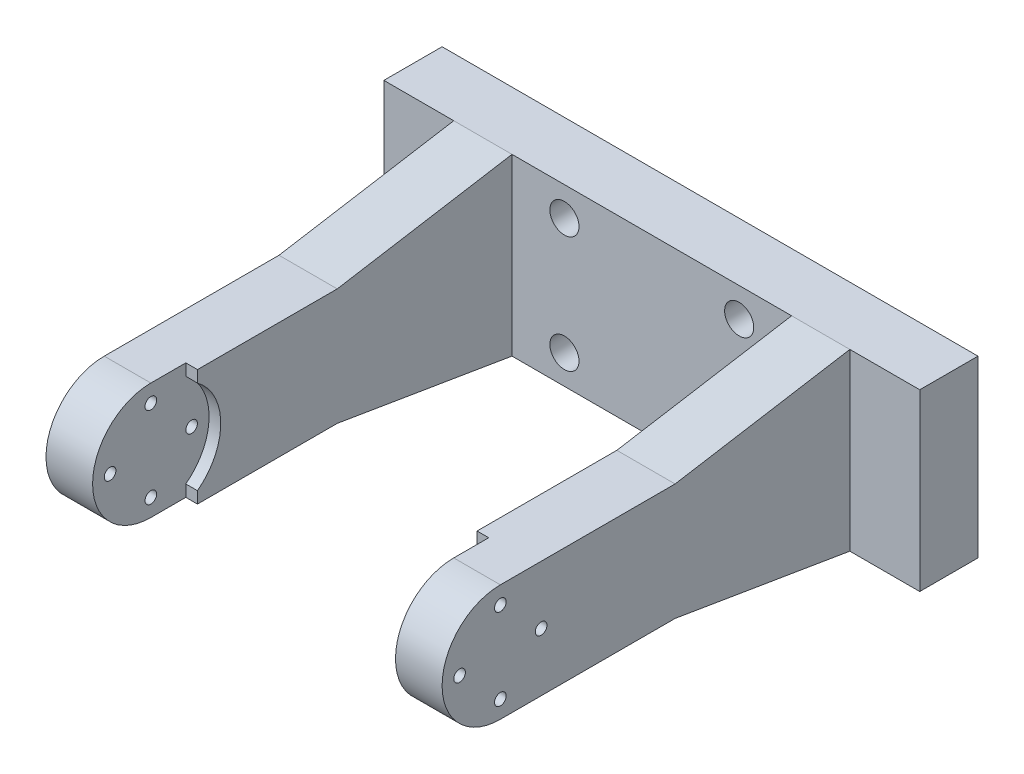
SolidWorks part; units mm, degrees
ref_plane "Front Plane" through (0, 0, 0) normal (0, 0, 1) x (1, 0, 0)
ref_plane "Top Plane" through (0, 0, 0) normal (0, 1, 0) x (1, 0, 0)
ref_plane "Right Plane" through (0, 0, 0) normal (1, 0, 0) x (0, 0, -1)
sketch "Sketch1" plane through (0, 0, 0) normal (0, 0, 1) x (1, 0, 0)
  line L1 (-46, -15) -> (46, -15)
  line L2 (-46, -15) -> (-46, 15)
  line L3 (-46, 15) -> (46, 15)
  line L4 (46, -15) -> (46, 15)
  line L5 (-46, -15) -> (46, 15) construction
  line L6 (-46, 15) -> (46, -15) construction
  point P0 (0, 0)
  dimension "D1" = 92
  dimension "D2" = 30
extrude "Boss-Extrude1" add sketch "Sketch1" along normal blind 10
sketch "Sketch2" plane through (46, 0, 0) normal (1, 0, 0) x (0, 0, -1)
  line L0 (-10, 15) -> (-40, 10)
  line L1 (-40, 10) -> (-70, 10)
  line L2 (-70, 10) -> (-70, -10) construction
  line L3 (-70, -10) -> (-40, -10)
  line L4 (-40, -10) -> (-10, -15)
  line L5 (0, -15) -> (0, 15) construction
  circle A0 centre (-70, 0) radius 10
  line M7 (-10, 15) -> (-10, -15)
  dimension "D1" = 20
  dimension "D2" = 70
  dimension "D3" = 30
extrude "Boss-Extrude2" add sketch "Sketch2" against normal blind 10 from offset 12 contours A0 L3 L4 L0 L1 M7 | A0 L2 | L2 A0 offset against normal yes
sketch "Sketch3" plane through (34, 0, 0) normal (1, 0, 0) x (0, 0, -1)
  circle A0 centre (-70, 0) radius 10 construction
  circle A1 centre (-70, 0) radius 7 construction
  circle A2 centre (-70, 7) radius 1
  circle A3 centre (-63, 0) radius 1
  circle A4 centre (-70, -7) radius 1
  circle A5 centre (-77, 0) radius 1
  dimension "D1" = 14
  dimension "D2" = 2
  dimension "D3" = 4
extrude "Cut-Extrude1" cut sketch "Sketch3" against normal blind 10
mirror "Mirror1" about plane through (0, 0, 0) normal (1, 0, 0) of "Boss-Extrude2", "Cut-Extrude1"
sketch "Sketch6" plane through (24, 0, 0) normal (-1, 0, 0) x (0, 0, 1)
  line L0 (70, 10) -> (64, 10)
  line L1 (40, 10) -> (70, 10) construction
  line L2 (64, 10) -> (64, 8)
  line L4 (64, -8) -> (64, -10)
  line L5 (70, -10) -> (40, -10) construction
  line L6 (64, -10) -> (70, -10)
  arc A0 (64, 8) -> (64, -8) centre (70, 0) ccw
  arc A1 (70, -10) -> (70, 10) centre (70, 0) ccw
  dimension "D1" = 2
extrude "Cut-Extrude2" cut sketch "Sketch6" against normal blind 2
mirror "Mirror2" about plane through (0, 0, 0) normal (1, 0, 0) of "Cut-Extrude2"
sketch "Sketch7" plane through (0, 0, 10) normal (0, 0, 1) x (1, 0, 0)
  line L0 (15, 10) -> (-15, 10) construction
  line L4 (-15, -10) -> (15, -10) construction
  circle A1 centre (-15, 10) radius 2.5
  circle A2 centre (15, 10) radius 2.5
  circle A4 centre (-15, -10) radius 2.5
  circle A5 centre (15, -10) radius 2.5
  point P11 (0, 10)
  dimension "D1" = 5
  dimension "D2" = 5
  dimension "D4" = 10
  dimension "D3" = 10
  dimension "D10" = 30
extrude "Cut-Extrude3" cut sketch "Sketch7" against normal up to surface (10 mm away) up to face at (0, 0, 0)
